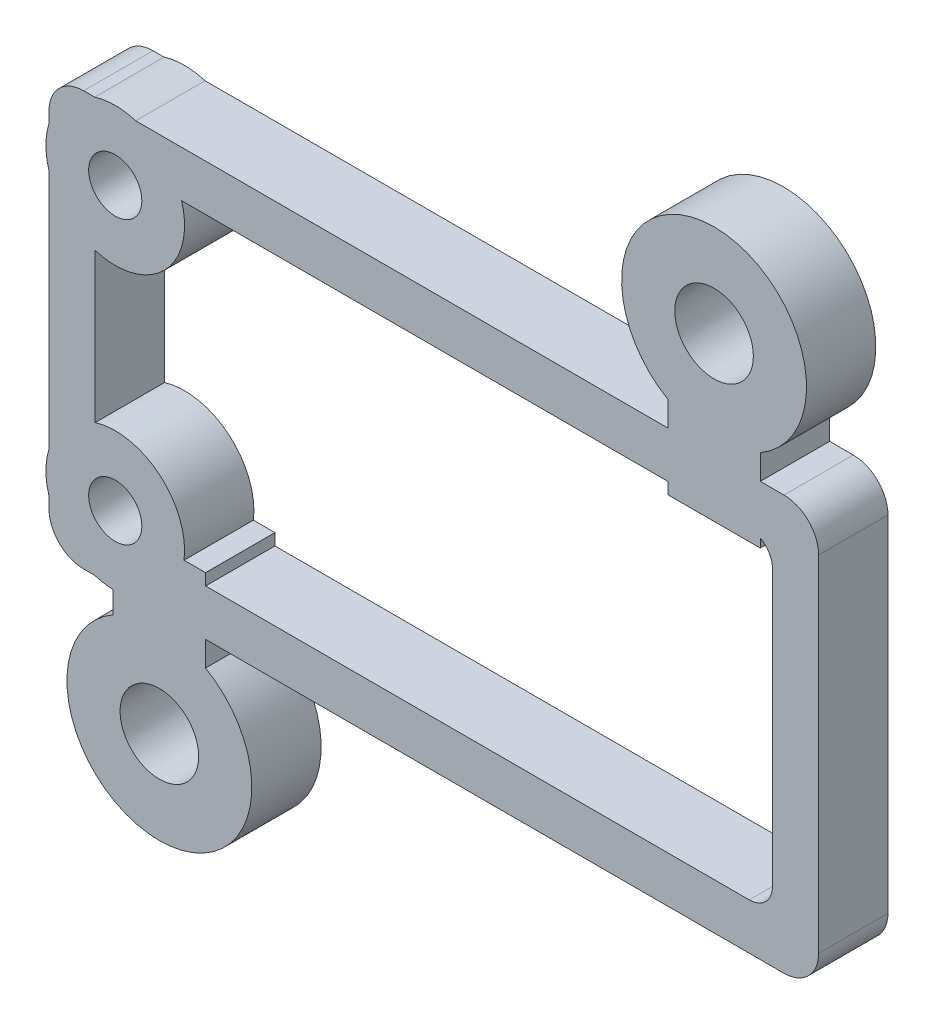
SolidWorks part; units mm, degrees
ref_plane "前视基准面" through (0, 0, 0) normal (0, 0, 1) x (1, 0, 0)
ref_plane "上视基准面" through (0, 0, 0) normal (0, 1, 0) x (1, 0, 0)
ref_plane "右视基准面" through (0, 0, 0) normal (1, 0, 0) x (0, 0, -1)
other "Configuration Table"
sketch "草图1" plane through (0, 0, 0) normal (0, 0, 1) x (1, 0, 0)
  line L0 (1, -0.5) -> (31.3, -0.5)
  line L1 (32.8, 1) -> (32.8, 15.92)
  line L2 (31.3, 17.42) -> (1, 17.42)
  line L3 (-0.5, 15.92) -> (-0.5, 1)
  line L4 (2.5, 1.5) -> (29.8, 1.5)
  line L5 (30.8, 2.5) -> (30.8, 14.42)
  line L6 (29.8, 15.42) -> (2.5, 15.42)
  line L7 (1.5, 14.42) -> (1.5, 2.5)
  arc A0 (31.3, -0.5) -> (32.8, 1) centre (31.3, 1) ccw
  arc A1 (32.8, 15.92) -> (31.3, 17.42) centre (31.3, 15.92) ccw
  arc A2 (1, 17.42) -> (-0.5, 15.92) centre (1, 15.92) ccw
  arc A3 (-0.5, 1) -> (1, -0.5) centre (1, 1) ccw
  arc A4 (29.8, 1.5) -> (30.8, 2.5) centre (29.8, 2.5) ccw
  arc A5 (30.8, 14.42) -> (29.8, 15.42) centre (29.8, 14.42) ccw
  arc A6 (2.5, 15.42) -> (1.5, 14.42) centre (2.5, 14.42) ccw
  arc A7 (1.5, 2.5) -> (2.5, 1.5) centre (2.5, 2.5) ccw
extrude "PCB_edge_support" add sketch "草图1" along normal blind 3
sketch "草图2" plane through (0, 0, 0) normal (0, 0, 1) x (1, 0, 0)
  circle A0 centre (2.365, 2.365) radius 3
  circle A1 centre (2.365, 14.555) radius 3
extrude "PCB_screw_lands" add sketch "草图2" along normal blind 3
sketch "草图3" plane through (0, 0, 0) normal (0, 0, 1) x (1, 0, 0)
  line L0 (2.275, -5.04) -> (6.275, -5.04)
  line L1 (6.275, -5.04) -> (6.275, 2)
  line L2 (6.275, 2) -> (2.275, 2)
  line L3 (2.275, 2) -> (2.275, -5.04)
  line L4 (26.275, 14.92) -> (30.275, 14.92)
  line L5 (30.275, 14.92) -> (30.275, 21.96)
  line L6 (30.275, 21.96) -> (26.275, 21.96)
  line L7 (26.275, 21.96) -> (26.275, 14.92)
extrude "Floating_mount_bridges" add sketch "草图3" along normal blind 3
sketch "草图4" plane through (0, 0, 0) normal (0, 0, 1) x (1, 0, 0)
  circle A0 centre (4.275, -5.04) radius 4
  circle A1 centre (28.275, 21.96) radius 4
extrude "Floating_mount_ears" add sketch "草图4" along normal blind 3
sketch "草图5" plane through (0, 0, 0) normal (0, 0, 1) x (1, 0, 0)
  circle A0 centre (2.365, 2.365) radius 1.15
  circle A1 centre (2.365, 14.555) radius 1.15
extrude "PCB_M2_clearance" cut sketch "草图5" along normal blind 4
sketch "草图6" plane through (0, 0, 0) normal (0, 0, 1) x (1, 0, 0)
  circle A0 centre (4.275, -5.04) radius 1.7
  circle A1 centre (28.275, 21.96) radius 1.7
extrude "M2_adjustment_0p7" cut sketch "草图6" along normal blind 4
